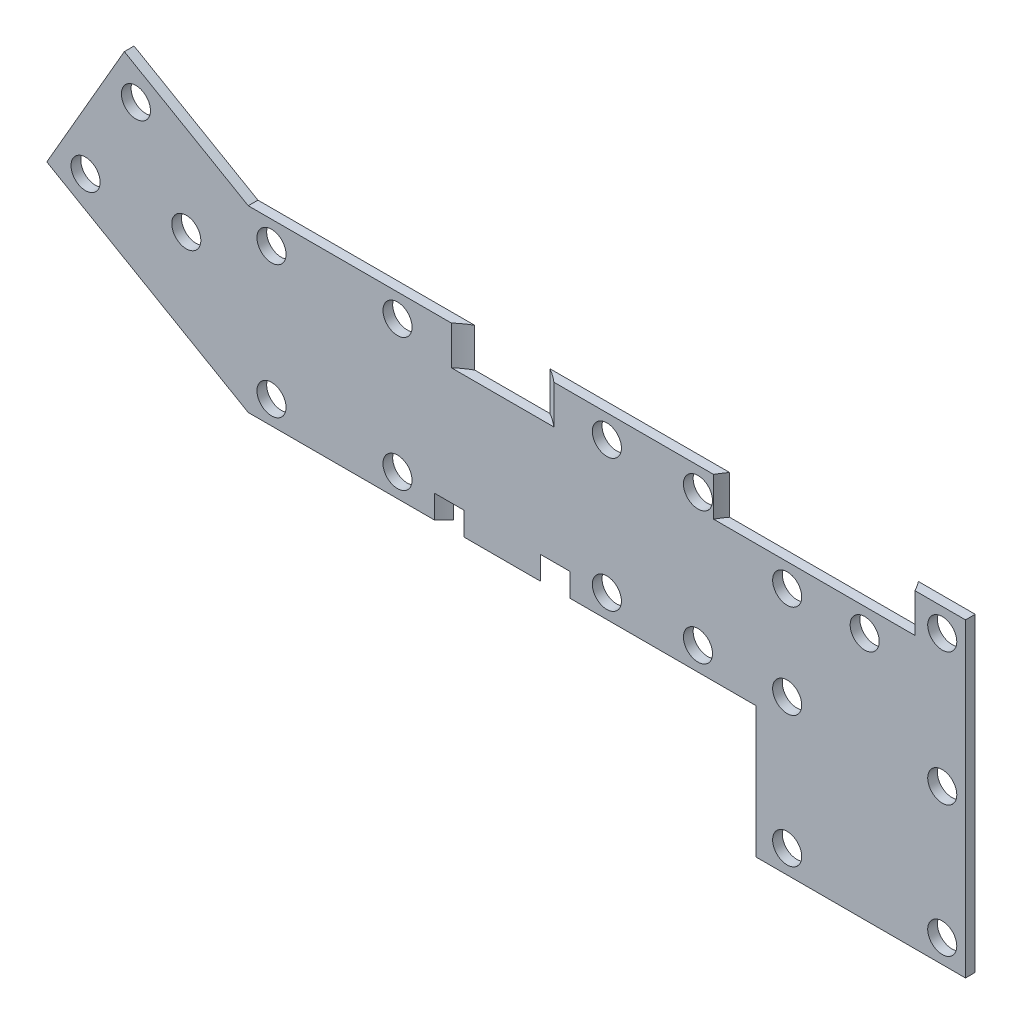
SolidWorks part; units mm, degrees
material "1023 Carbon Steel Sheet (SS)"
ref_plane "Front Plane" through (0, 0, 0) normal (0, 0, 1) x (1, 0, 0)
ref_plane "Top Plane" through (0, 0, 0) normal (0, 1, 0) x (1, 0, 0)
ref_plane "Right Plane" through (0, 0, 0) normal (1, 0, 0) x (0, 0, -1)
sketch "Sketch1" plane through (0, 0, 0) normal (0, 0, 1) x (1, 0, 0)
  line L0 (0, 0) -> (-40.5911, 23.4353)
  line L1 (-40.5911, 23.4353) -> (-65.9911, -20.5588)
  line L2 (-65.9911, -20.5588) -> (0, -58.6588)
  line L3 (0, -58.6588) -> (64.135, -58.6588)
  line L4 (64.135, -58.6588) -> (64.135, -51.0388)
  line L5 (64.135, -51.0388) -> (70.612, -51.0388)
  line L6 (70.612, -51.0388) -> (70.612, -58.6588)
  line L7 (70.612, -58.6588) -> (95.758, -58.6588)
  line L8 (95.758, -58.6588) -> (95.758, -51.0388)
  line L9 (95.758, -51.0388) -> (102.235, -51.0388)
  line L10 (102.235, -51.0388) -> (102.235, -58.6588)
  line L11 (102.235, -58.6588) -> (166.37, -58.6588)
  line L12 (166.37, -58.6588) -> (166.37, -101.6)
  line L13 (166.37, -101.6) -> (234.95, -101.6)
  line L14 (234.95, -101.6) -> (234.95, 0)
  line L23 (234.95, 0) -> (0, 0)
  circle A1 centre (-20.2956, -17.6117) radius 4.7625
  circle A2 centre (-53.2911, -17.6117) radius 4.7625
  circle A3 centre (-36.7934, 10.9633) radius 4.7625
  circle A4 centre (-36.7934, -8.0867) radius 19.05 construction
  circle A5 centre (7.62, -51.0388) radius 4.7625
  circle A6 centre (7.62, -7.62) radius 4.7625
  circle A7 centre (48.895, -7.62) radius 4.7625
  circle A8 centre (117.475, -7.62) radius 4.7625
  circle A9 centre (147.32, -7.62) radius 4.7625
  circle A10 centre (117.475, -51.0388) radius 4.7625
  circle A11 centre (48.895, -51.0388) radius 4.7625
  circle A12 centre (147.32, -51.0388) radius 4.7625
  circle A13 centre (176.53, -20.32) radius 4.7625
  circle A14 centre (201.93, -20.32) radius 4.7625
  circle A15 centre (227.33, -7.62) radius 4.7625
  circle A16 centre (227.33, -93.98) radius 4.7625
  circle A17 centre (176.53, -93.98) radius 4.7625
  circle A18 centre (227.33, -51.0388) radius 4.7625
  circle A19 centre (176.53, -51.0388) radius 4.7625
  point P3 (-36.7934, -8.0867)
  point P28 (-53.2911, 1.4383)
  point P33 (83.185, -58.6588)
  dimension "D18" = 9.525
  dimension "D21" = 3
  dimension "D16" = 38.1
  dimension "D17" = 7.62
  dimension "D1" = 30
  dimension "D2" = 76.2
  dimension "D3" = 50.8
  dimension "D4" = 83.185
  dimension "D5" = 234.95
  dimension "D6" = 38.1
  dimension "D7" = 29.845
  dimension "D8" = 25.146
  dimension "D9" = 166.37
  dimension "D10" = 7.62
  dimension "D11" = 20.32
  dimension "D12" = 29.21
  dimension "D13" = 101.6
  dimension "D14" = 25.4
  dimension "D15" = 7.62
  dimension "D19" = 19.05
  dimension "D20" = 25.4
  dimension "D22" = 7.62
  dimension "D23" = 7.62
  dimension "D24" = 34.29
  dimension "D25" = 34.29
  dimension "D30" = 7.62
  dimension "D32" = 7.62
extrude "Boss-Extrude1" add sketch "Sketch1" along normal blind 3.175
sketch "Sketch2" plane through (0, -58.6588, 0) normal (0, -1, 0) x (1, 0, 0)
  line L0 (70.612, 3.175) -> (95.758, 3.175) construction
  line L3 (83.185, 3.175) -> (83.185, 22.225) construction
  line L4 (70.612, 3.175) -> (95.758, 3.175) construction
  circle A0 centre (83.185, 22.225) radius 22.86
  circle A1 centre (83.185, 22.225) radius 29.21
  dimension "D2" = 45.72
  dimension "D3" = 6.35
  dimension "D1" = 19.05
extrude "Cut-Extrude1" cut sketch "Sketch2" against normal blind 7.62
sketch "Sketch5" plane through (0, 0, 0) normal (0, 1, 0) x (1, 0, 0)
  line L0 (234.95, -1.5875) -> (185.42, -1.5875) construction
  line L1 (234.95, -3.175) -> (234.95, 0) construction
  line L2 (185.42, -3.175) -> (185.42, -22.225) construction
  line L4 (234.95, -3.175) -> (0, -3.175) construction
  line L5 (0, -1.5875) -> (83.312, -1.5875) construction
  line L6 (0, -3.175) -> (0, 0) construction
  circle A0 centre (185.42, -22.225) radius 38.1
  circle A1 centre (83.312, -22.225) radius 25.4
  dimension "D3" = 76.2
  dimension "D5" = 50.8
  dimension "D1" = 49.53
  dimension "D2" = 19.05
  dimension "D4" = 83.312
extrude "Cut-Extrude5" cut sketch "Sketch5" against normal blind 12.7
